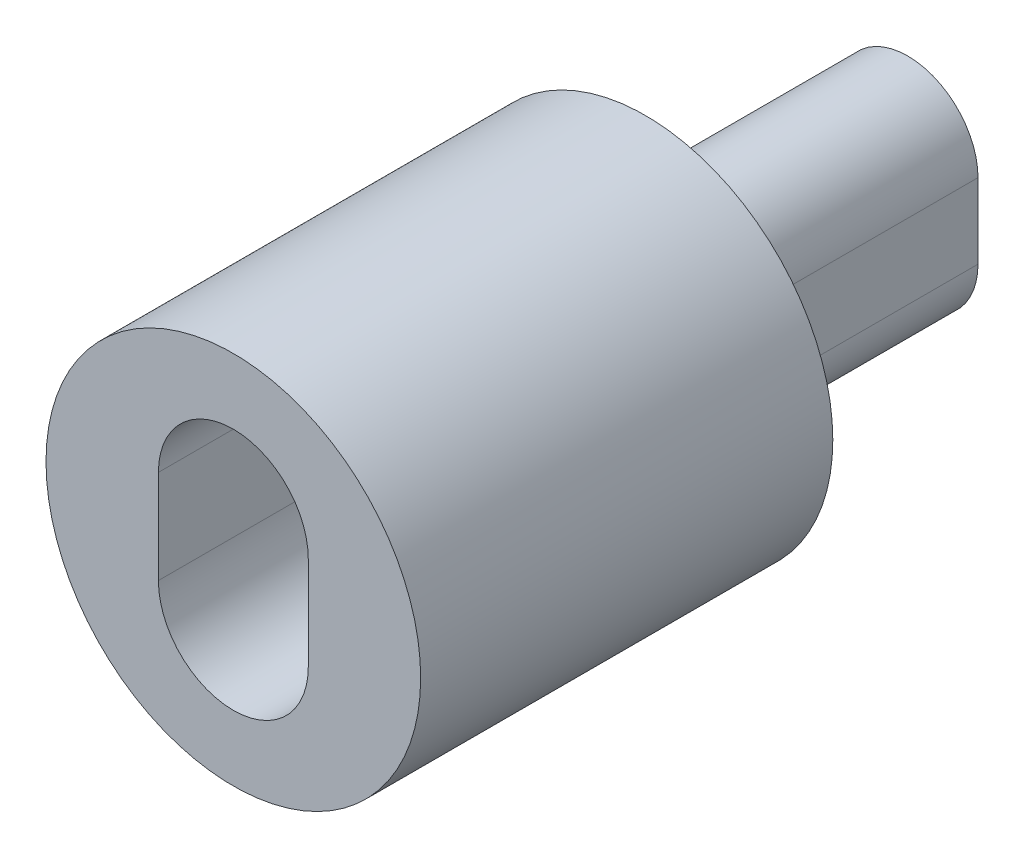
SolidWorks part; units mm, degrees
ref_plane "Plan de face" through (0, 0, 0) normal (0, 0, 1) x (1, 0, 0)
ref_plane "Plan de dessus" through (0, 0, 0) normal (0, 1, 0) x (1, 0, 0)
ref_plane "Plan de droite" through (0, 0, 0) normal (1, 0, 0) x (0, 0, -1)
sketch "Sketch1" plane through (0, 0, 0) normal (0, 0, 1) x (1, 0, 0)
  line L0 (-12.3173, -14.3923) -> (-12.3173, -35.1101) construction
  line L1 (-12.3173, -23.1161) -> (-23.2709, -23.1161) construction
  line L2 (-23.2709, -23.1161) -> (-12.3173, -23.1161) construction
  line L3 (-12.3173, -23.1161) -> (-2.4166, -23.1161) construction
  circle A0 centre (-12.3173, -23.1161) radius 5
extrude "Boss-Extrude1" add sketch "Sketch1" along normal blind 11
ref_plane "Plane1" through (0, 0, 11) normal (0, 0, 1) x (1, 0, 0)
sketch "Sketch2" plane through (0, 0, 11) normal (0, 0, 1) x (1, 0, 0)
  line L0 (-12.3173, -24.3661) -> (-12.3173, -21.8661) construction
  line L3 (-14.3173, -24.3661) -> (-14.3173, -21.8661)
  line L4 (-10.3173, -24.3661) -> (-10.3173, -21.8661)
  line L5 (-12.3173, -18.1161) -> (-12.3173, -28.1161) construction
  line L6 (-17.3173, -23.1161) -> (-7.3173, -23.1161) construction
  arc A2 (-14.3173, -24.3661) -> (-10.3173, -24.3661) centre (-12.3173, -24.3661) ccw
  arc A3 (-10.3173, -21.8661) -> (-14.3173, -21.8661) centre (-12.3173, -21.8661) ccw
  circle A4 centre (-12.3173, -23.1161) radius 5 construction
  point P3 (-12.3173, -23.1161)
  dimension "D1" = 1.25
  dimension "D2" = 1.25
  dimension "D3" = 4
  dimension "D4" = 5
  dimension "D5" = 5
  dimension "D6" = 5
  dimension "D7" = 5
extrude "Cut-Extrude1" cut sketch "Sketch2" against normal blind 8
sketch "Sketch4" plane through (0, 0, 0) normal (0, 0, -1) x (-1, 0, 0)
  line L0 (12.3173, -24.1161) -> (12.3173, -22.1161) construction
  line L5 (10.4423, -24.1161) -> (10.4423, -22.1161)
  line L6 (14.1923, -24.1161) -> (14.1923, -22.1161)
  line L7 (12.3173, -18.1161) -> (12.3173, -28.1161) construction
  arc A5 (10.4423, -24.1161) -> (14.1923, -24.1161) centre (12.3173, -24.1161) ccw
  arc A6 (14.1923, -22.1161) -> (10.4423, -22.1161) centre (12.3173, -22.1161) ccw
  circle A8 centre (12.3173, -23.1161) radius 5 construction
  point P2 (12.3173, -23.1161)
  dimension "D1" = 1
  dimension "D3" = 5
  dimension "D2" = 3.75
  dimension "D4" = 5
extrude "Boss-Extrude2" add sketch "Sketch4" along normal blind 7
